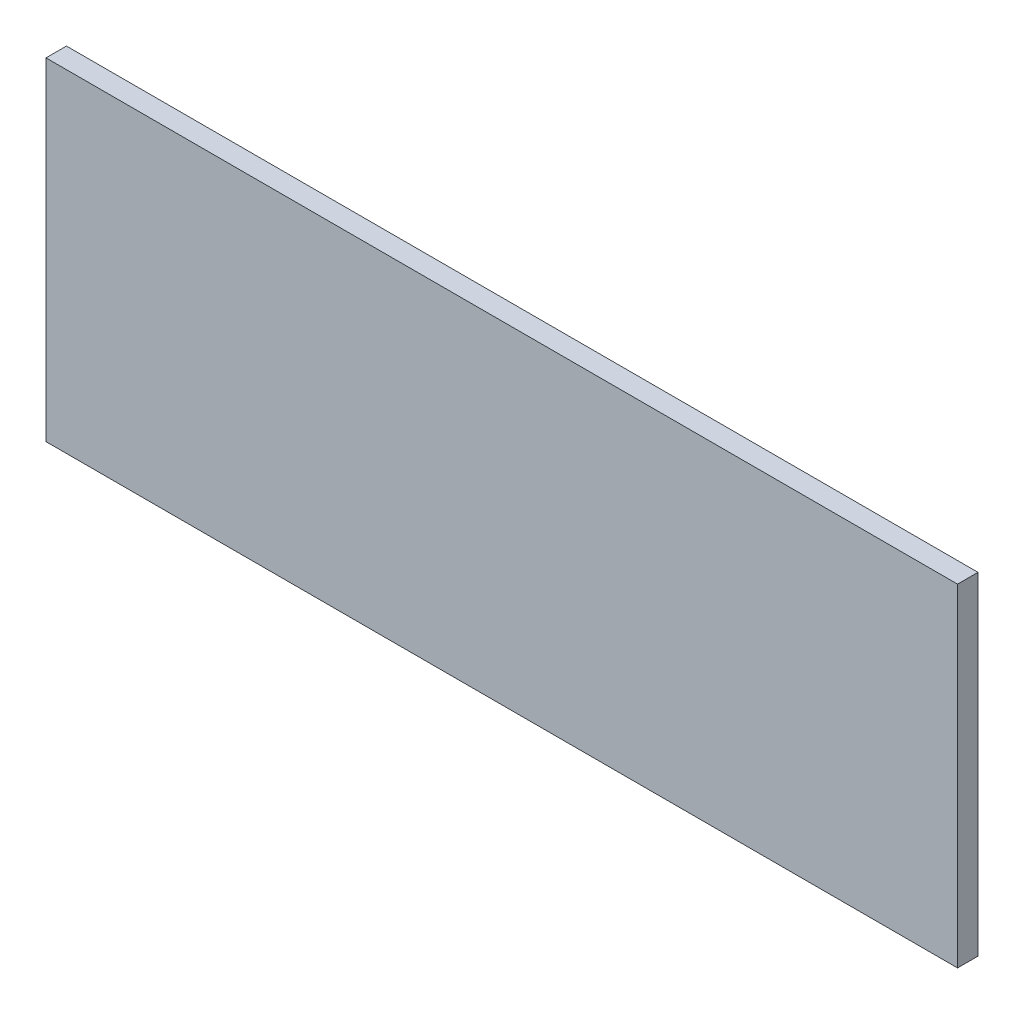
SolidWorks part; units mm, degrees
material "Q235A"
ref_plane "前视" through (0, 0, 0) normal (0, 0, 1) x (1, 0, 0)
ref_plane "上视" through (0, 0, 0) normal (0, 1, 0) x (1, 0, 0)
ref_plane "右视" through (0, 0, 0) normal (1, 0, 0) x (0, 0, -1)
sketch "草图1" plane through (0, 0, 0) normal (0, 0, 1) x (1, 0, 0)
  line L1 (356.5, -130) -> (-356.5, -130)
  line L2 (356.5, -130) -> (356.5, 130)
  line L3 (356.5, 130) -> (-356.5, 130)
  line L4 (-356.5, -130) -> (-356.5, 130)
  line L5 (356.5, -130) -> (-356.5, 130) construction
  line L6 (356.5, 130) -> (-356.5, -130) construction
  point P0 (0, 0)
  dimension "D1" = 260
  dimension "D2" = 713
extrude "凸台-拉伸1" add sketch "草图1" along normal blind 16
